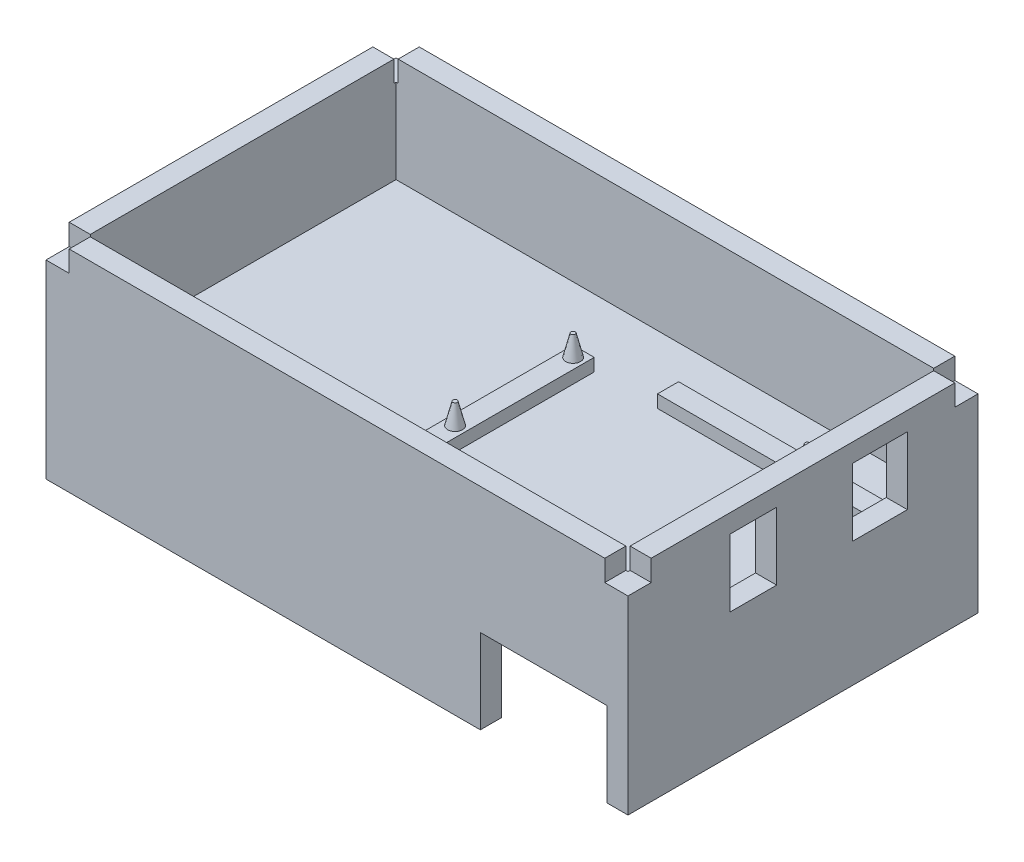
SolidWorks part; units mm, degrees
ref_plane "Ebene vorne" through (0, 0, 0) normal (0, 0, 1) x (1, 0, 0)
ref_plane "Ebene oben" through (0, 0, 0) normal (0, 1, 0) x (1, 0, 0)
ref_plane "Ebene rechts" through (0, 0, 0) normal (1, 0, 0) x (0, 0, -1)
sketch "Sketch1" plane through (0, 0, 0) normal (0, 1, 0) x (1, 0, 0)
  line L1 (-69, -41.5) -> (69, -41.5)
  line L2 (-69, -41.5) -> (-69, 41.5)
  line L3 (-69, 41.5) -> (69, 41.5)
  line L4 (69, -41.5) -> (69, 41.5)
  line L5 (-69, -41.5) -> (69, 41.5) construction
  line L6 (-69, 41.5) -> (69, -41.5) construction
  point P0 (0, 0)
  dimension "D1" = 138
  dimension "D2" = 83
extrude "Boss-Extrude1" add sketch "Sketch1" along normal blind 5
sketch "Sketch2" plane through (0, 0, 0) normal (0, -1, 0) x (1, 0, 0)
  line L1 (-69, -41.5) -> (69, -41.5)
  line L2 (-69, -41.5) -> (-69, 41.5)
  line L3 (-69, 41.5) -> (69, 41.5)
  line L4 (69, -41.5) -> (69, 41.5)
  line L5 (-69, -41.5) -> (69, 41.5) construction
  line L6 (-69, 41.5) -> (69, -41.5) construction
  line L7 (-64, -36.5) -> (64, -36.5)
  line L8 (-64, -36.5) -> (-64, 36.5)
  line L9 (-64, 36.5) -> (64, 36.5)
  line L10 (64, -36.5) -> (64, 36.5)
  line L11 (-64, -36.5) -> (64, 36.5) construction
  line L12 (-64, 36.5) -> (64, -36.5) construction
  point P0 (0, 0)
  point P5 (0, 0)
  dimension "D1" = 128
  dimension "D2" = 73
extrude "Boss-Extrude2" add sketch "Sketch2" along normal blind 20
sketch "Sketch3" plane through (0, 0, 36.5) normal (0, 0, -1) x (-1, 0, 0)
  line L0 (-64, -20) -> (64, -20) construction
  line L1 (-64, 0) -> (-34, 0)
  line L2 (-64, 0) -> (-64, -20)
  line L3 (-64, -20) -> (-34, -20)
  line L4 (-34, 0) -> (-34, -20)
  dimension "D1" = 30
extrude "Cut-Extrude1" cut sketch "Sketch3" against normal up to next
sketch "Sketch4" plane through (0, 5, 0) normal (0, 1, 0) x (1, 0, 0)
  line L0 (34, -36.5) -> (-64, -36.5) construction
  line L1 (69, 41.5) -> (-69, 41.5)
  line L2 (69, 41.5) -> (69, -41.5)
  line L3 (69, -41.5) -> (-69, -41.5)
  line L4 (-69, 41.5) -> (-69, -41.5)
  line L5 (69, 41.5) -> (-69, -41.5) construction
  line L6 (69, -41.5) -> (-69, 41.5) construction
  line L7 (64, 36.5) -> (-64, 36.5)
  line L8 (64, 36.5) -> (64, -36.5)
  line L9 (64, -36.5) -> (-64, -36.5)
  line L10 (-64, 36.5) -> (-64, -36.5)
  line L11 (64, 36.5) -> (-64, -36.5) construction
  line L12 (64, -36.5) -> (-64, 36.5) construction
  line L13 (64, 36.5) -> (64, -41.5) construction
  point P0 (0, 0)
  point P5 (0, 0)
  dimension "D1" = 0
  dimension "D2" = 0
extrude "Boss-Extrude3" add sketch "Sketch4" along normal blind 25
sketch "Sketch5" plane through (0, 5, 0) normal (0, 1, 0) x (1, 0, 0)
  line L0 (64, -28.5) -> (14, -28.5)
  line L1 (64, -28.5) -> (64, -23.5)
  line L2 (14, -28.5) -> (14, -23.5)
  line L3 (64, -23.5) -> (14, -23.5)
  line L5 (64, -36.5) -> (64, 36.5) construction
  line L6 (64, 20.5) -> (14, 20.5)
  line L7 (64, 20.5) -> (64, 25.5)
  line L8 (14, 20.5) -> (14, 25.5)
  line L9 (64, 25.5) -> (14, 25.5)
  line L10 (-1, 20.5) -> (-1, -14.5)
  line L11 (-1, 20.5) -> (-6, 20.5)
  line L12 (-1, -14.5) -> (-6, -14.5)
  line L13 (-6, 20.5) -> (-6, -14.5)
  line L14 (64, 36.5) -> (-64, 36.5) construction
  line L15 (64, 36.5) -> (-64, 36.5) construction
  dimension "D1" = 44
  dimension "D2" = 5
  dimension "D3" = 5
  dimension "D4" = 5
  dimension "D5" = 50
  dimension "D6" = 0
  dimension "D7" = 35
  dimension "D8" = 65
  dimension "D9" = 16
  dimension "D10" = 11
extrude "Boss-Extrude10" add sketch "Sketch5" along normal blind 3
sketch "Sketch6" plane through (0, 8, 0) normal (0, 1, 0) x (1, 0, 0)
  line L0 (64, 23) -> (14, 23) construction
  line L1 (64, 20.5) -> (64, 25.5) construction
  line L2 (14, 25.5) -> (14, 20.5) construction
  line L4 (-3.5, -14.5) -> (-3.5, 20.5) construction
  line L5 (-6, -14.5) -> (-1, -14.5) construction
  line L6 (-1, 20.5) -> (-6, 20.5) construction
  line L7 (64, -26) -> (14, -26) construction
  line L8 (64, -28.5) -> (64, -23.5) construction
  line L9 (14, -23.5) -> (14, -28.5) construction
  line L10 (64, -23.5) -> (64, 20.5) construction
  circle A0 centre (47, 23) radius 1.75
  circle A1 centre (47, -26) radius 1.75
  circle A2 centre (-3.5, 18) radius 1.75
  circle A3 centre (-3.5, -10) radius 1.75
  point P28 (0, 0)
  point P29 (0, 0)
  dimension "D1" = 17
  dimension "D2" = 3.5
  dimension "D3" = 0
  dimension "D4" = 3.5
  dimension "D5" = 67.5
  dimension "D6" = 3.5
  dimension "D9" = 28
  dimension "D10" = 3.5
  dimension "D8" = 5
  dimension "D11" = 49
  dimension "D12" = 50.5
extrude "Boss-Extrude11" add sketch "Sketch6" along normal blind 5 draft 14
sketch "Sketch7" plane through (64, 0, 0) normal (-1, 0, 0) x (0, 0, 1)
  line L0 (-24.75, 9.6) -> (-24.75, 25.6)
  line L1 (-24.75, 9.6) -> (-11.75, 9.6)
  line L2 (-24.75, 25.6) -> (-11.75, 25.6)
  line L3 (-11.75, 9.6) -> (-11.75, 25.6)
  line L7 (23.5, 5) -> (-20.5, 5) construction
  dimension "D1" = 0
  dimension "D2" = 13
  dimension "D3" = 4.6
  dimension "D4" = 16
extrude "Cut-Extrude2" cut sketch "Sketch7" against normal up to next
sketch "Sketch8" plane through (64, 0, 0) normal (-1, 0, 0) x (0, 0, 1)
  line L0 (6.25, 9.6) -> (17.25, 9.6)
  line L1 (6.25, 9.6) -> (6.25, 25.6)
  line L2 (17.25, 9.6) -> (17.25, 25.6)
  line L3 (6.25, 25.6) -> (17.25, 25.6)
  line L4 (-24.75, 9.6) -> (-11.75, 9.6) construction
  line L5 (-11.75, 25.6) -> (-24.75, 25.6) construction
  point P4 (6.25, 17.6)
  dimension "D1" = 31
  dimension "D2" = 0
  dimension "D3" = 11
  dimension "D4" = 0
  dimension "D5" = 16
  dimension "D6" = 16
extrude "Cut-Extrude3" cut sketch "Sketch8" against normal up to next
sketch "Sketch11" plane through (0, 30, 0) normal (0, 1, 0) x (1, 0, 0)
  line L0 (-63.5, 36) -> (-63.5, 41.5)
  line L1 (-63.5, 36) -> (-69, 36)
  line L2 (-63.5, 41.5) -> (-69, 41.5)
  line L3 (-69, 36) -> (-69, 41.5)
  line L4 (69, 41.5) -> (-69, 41.5) construction
  line L5 (-63.5, -36) -> (-63.5, -41.5)
  line L6 (-63.5, -36) -> (-69, -36)
  line L7 (-63.5, -41.5) -> (-69, -41.5)
  line L8 (-69, -36) -> (-69, -41.5)
  line L9 (-69, -41.5) -> (69, -41.5) construction
  line L10 (63.5, -36) -> (63.5, -41.5)
  line L11 (63.5, -36) -> (69, -36)
  line L12 (63.5, -41.5) -> (69, -41.5)
  line L13 (69, -36) -> (69, -41.5)
  line L14 (63.5, 36) -> (63.5, 41.5)
  line L15 (63.5, 36) -> (69, 36)
  line L16 (63.5, 41.5) -> (69, 41.5)
  line L17 (69, 36) -> (69, 41.5)
  line L18 (-69, 41.5) -> (-69, -41.5) construction
  line L19 (69, -41.5) -> (69, 41.5) construction
  dimension "D1" = 0
  dimension "D2" = 0
  dimension "D3" = 0
  dimension "D4" = 0
  dimension "D5" = 5.5
  dimension "D6" = 5.5
  dimension "D7" = 5.5
  dimension "D8" = 5.5
  dimension "D9" = 5.5
  dimension "D10" = 5.5
  dimension "D11" = 5.5
  dimension "D12" = 5.5
extrude "Cut-Extrude7" cut sketch "Sketch11" against normal blind 5
